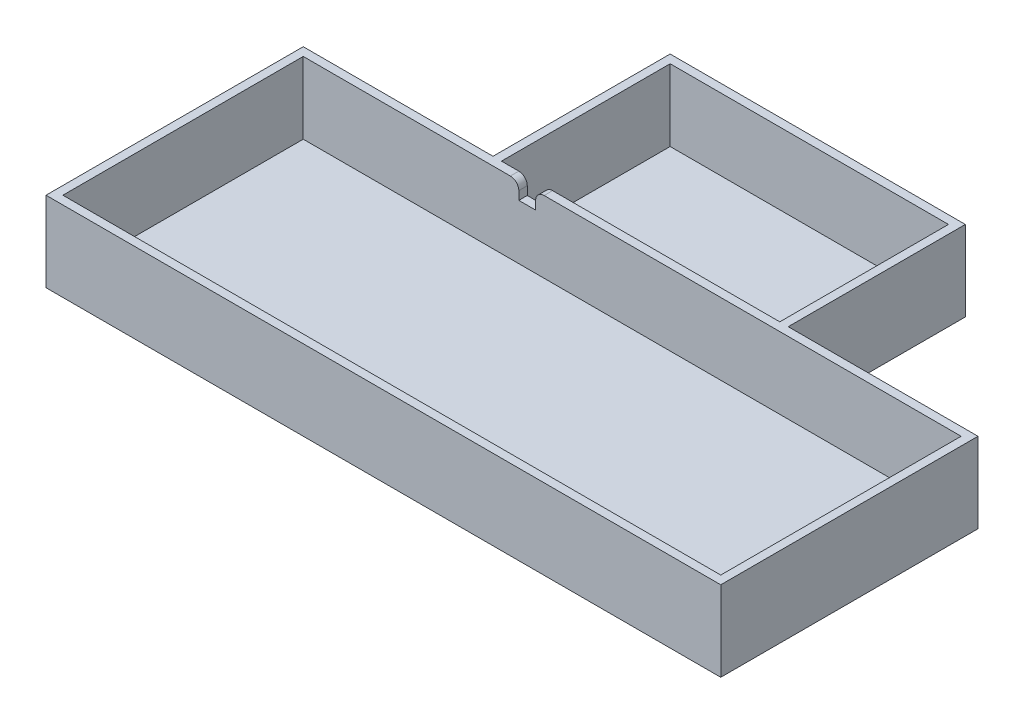
SolidWorks part; units mm, degrees
ref_plane "Front Plane" through (0, 0, 0) normal (0, 0, 1) x (1, 0, 0)
ref_plane "Top Plane" through (0, 0, 0) normal (0, 1, 0) x (1, 0, 0)
ref_plane "Right Plane" through (0, 0, 0) normal (1, 0, 0) x (0, 0, -1)
sketch "Sketch1" plane through (0, 0, 0) normal (0, 1, 0) x (1, 0, 0)
  line L1 (0, 0) -> (160, 0)
  line L2 (0, 0) -> (0, -61)
  line L3 (0, -61) -> (160, -61)
  line L4 (160, 0) -> (160, -61)
  dimension "D1" = 160
  dimension "D2" = 61
extrude "Boss-Extrude1" add sketch "Sketch1" along normal blind 2
sketch "Sketch2" plane through (0, 2, 0) normal (0, 1, 0) x (1, 0, 0)
  line L0 (160, -61) -> (160, 0) construction
  line L1 (0, 0) -> (160, 0)
  line L2 (0, 0) -> (0, -2)
  line L3 (0, -2) -> (160, -2)
  line L4 (160, 0) -> (160, -2)
  point P7 (160, 0)
  dimension "D1" = 2
extrude "Boss-Extrude2" add sketch "Sketch2" along normal blind 17 contours L3 L4 L1 L2
sketch "Sketch3" plane through (0, 2, 0) normal (0, 1, 0) x (1, 0, 0)
  line L0 (0, -2) -> (160, -2) construction
  line L1 (0, -61) -> (2, -61)
  line L2 (0, -61) -> (0, -2)
  line L3 (0, -2) -> (2, -2)
  line L4 (2, -61) -> (2, -2)
  line L5 (0, -2) -> (160, -2) construction
  line L6 (160, -61) -> (158, -61)
  line L7 (160, -61) -> (160, -2)
  line L8 (160, -2) -> (158, -2)
  line L9 (158, -61) -> (158, -2)
  line L11 (2, -61) -> (158, -61)
  line L12 (2, -61) -> (2, -59)
  line L13 (2, -59) -> (158, -59)
  line L14 (158, -61) -> (158, -59)
  line M6 (160, -2) -> (0, -2)
  line M7 (0, -2) -> (0, -61)
  line M8 (0, -61) -> (160, -61)
  line M9 (160, -61) -> (160, -2)
  dimension "D1" = 2
  dimension "D2" = 2
  dimension "D3" = 2
extrude "Boss-Extrude3" add sketch "Sketch3" along normal blind 17 contours L4 M8 M6 M7 | L9 M8 M9 M6 | L13 L4 L9 M8
sketch "Sketch4" plane through (0, 0, 0) normal (0, 0, -1) x (-1, 0, 0)
  line L0 (-160, 0) -> (0, 0) construction
  line L1 (-115, -2) -> (-45, -2)
  line L2 (-115, -2) -> (-115, 2)
  line L3 (-115, 2) -> (-45, 2)
  line L4 (-45, -2) -> (-45, 2)
  line L5 (-115, -2) -> (-45, 2) construction
  line L6 (-115, 2) -> (-45, -2) construction
  line L7 (-45, 0) -> (-115, 0)
  point P0 (-80, 0)
  line M5 (-160, 0) -> (0, 0)
  dimension "D1" = 4
  dimension "D2" = 70
extrude "Boss-Extrude4" add sketch "Sketch4" along normal blind 42 contours L4 L3 L2 M5
sketch "Sketch5" plane through (0, 0, 0) normal (0, 0, -1) x (-1, 0, 0)
  line L0 (0, 19) -> (-160, 19) construction
  line L1 (-57.1169, 23) -> (-53.1169, 23)
  line L2 (-57.1169, 23) -> (-57.1169, 15)
  line L3 (-57.1169, 15) -> (-53.1169, 15)
  line L4 (-53.1169, 23) -> (-53.1169, 15)
  line L5 (-57.1169, 23) -> (-53.1169, 15) construction
  line L6 (-57.1169, 15) -> (-53.1169, 23) construction
  point P0 (-55.1169, 19)
  dimension "D1" = 8
  dimension "D2" = 4
extrude "Cut-Extrude1" cut sketch "Sketch5" against normal blind 39 contours L3 L4 L1 L2
fillet "Fillet1" radius 2 2 edges at (53.1169, 19, 1) (57.1169, 19, 1)
sketch "Sketch6" plane through (0, 2, 0) normal (0, 1, 0) x (1, 0, 0)
  line L0 (59.1169, 0) -> (160, 0) construction
  line L1 (115, 42) -> (113, 42)
  line L2 (115, 42) -> (115, 0)
  line L3 (115, 0) -> (113, 0)
  line L4 (113, 42) -> (113, 0)
  line L5 (0, 0) -> (51.1169, 0) construction
  line L6 (45, 42) -> (47, 42)
  line L7 (45, 42) -> (45, 0)
  line L8 (45, 0) -> (47, 0)
  line L9 (47, 42) -> (47, 0)
  point P14 (0, 0)
  dimension "D1" = 2
  dimension "D2" = 2
extrude "Boss-Extrude5" add sketch "Sketch6" along normal blind 17 contours L4 L3 L2 L1
sketch "Sketch9" plane through (0, 2, 0) normal (0, 1, 0) x (1, 0, 0)
  line L0 (113, 0) -> (45, 0) construction
  line L1 (45, 42) -> (47, 42)
  line L2 (45, 42) -> (45, 0)
  line L3 (45, 0) -> (47, 0)
  line L4 (47, 42) -> (47, 0)
  line L6 (113, 42) -> (47, 42)
  line L7 (113, 42) -> (113, 40)
  line L8 (113, 40) -> (47, 40)
  line L9 (47, 42) -> (47, 40)
  line M3 (45, 0) -> (113, 0)
  line M4 (113, 0) -> (113, 42)
  line M5 (113, 42) -> (45, 42)
  line M6 (45, 42) -> (45, 0)
  dimension "D1" = 2
  dimension "D2" = 2
extrude "Boss-Extrude6" add sketch "Sketch9" along normal blind 17 contours L4 M5 M6 M3 | L8 L4 M4 M5
